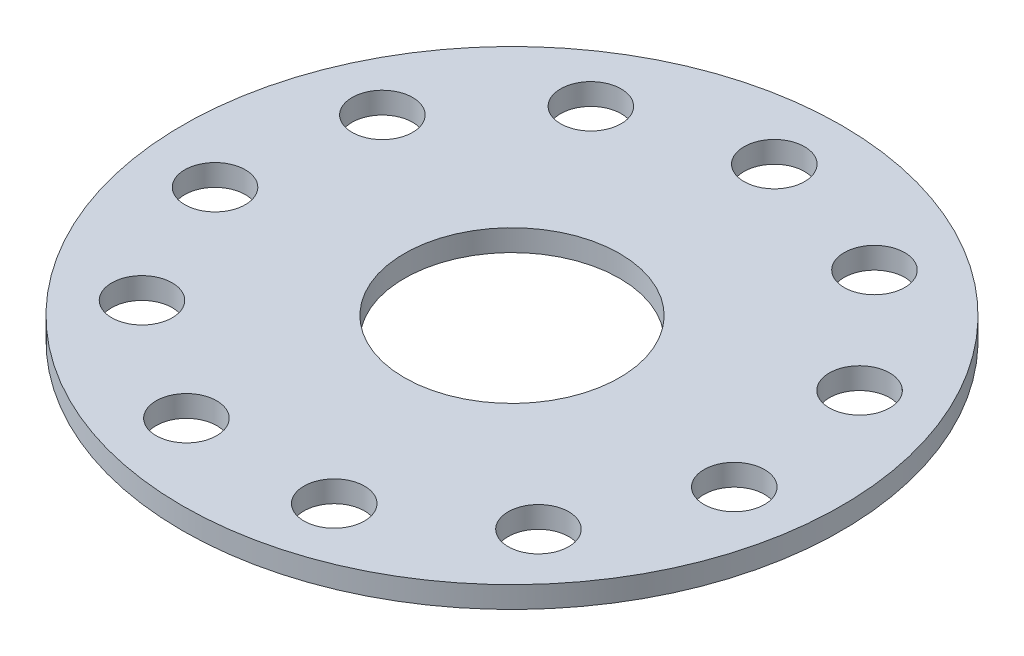
SolidWorks part; units mm, degrees
material "6061 Alloy"
ref_plane "Front Plane" through (0, 0, 0) normal (0, 0, 1) x (1, 0, 0)
ref_plane "Top Plane" through (0, 0, 0) normal (0, 1, 0) x (1, 0, 0)
ref_plane "Right Plane" through (0, 0, 0) normal (1, 0, 0) x (0, 0, -1)
sketch "Sketch1" plane through (0, 0, 0) normal (0, 1, 0) x (1, 0, 0)
  circle A0 centre (0, 0) radius 24.5
  circle A9 centre (0, 0) radius 8
  point P7 (0, 24.5)
  dimension "D1" = 49
  dimension "D2" = 16
extrude "Boss-Extrude1" add sketch "Sketch1" along normal blind 1.6002
sketch "Sketch3" plane through (0, 1.6002, 0) normal (0, 1, 0) x (1, 0, 0)
  line L53 (0, 19.5) -> (0, 24.5) construction
  circle A0 centre (0, 19.5) radius 2.25
  circle A3 centre (0, 0) radius 24.5 construction
  dimension "D1" = 4.5
  dimension "D2" = 5
extrude "Cut-Extrude1" cut sketch "Sketch3" against normal through all
pattern_circular "CirPattern1" count 11 over 360 about axis through (0, 0, 0) along (0, 1, 0) of "Cut-Extrude1"
equation "\"shaft_diameter\"=12"
equation "\"outerdiameter\"=49"
equation "\"numberofbars\"= 11"
equation "\"t\"= 20"
equation "\"width\"=1.5"
equation "\"bardiameter\"= 4.50"
equation "\"D1@Sketch1\"=\"outerdiameter\""
equation "\"centerdepth\"= 5"
equation "\"D1@Boss-Extrude1\"= \"t\""
equation "\"key_width\"=4"
equation "\"key_height\"= 2.5"
equation "\"D2@Sketch3\"=\"centerdepth\""
equation "\"RF1\"= 0.25"
equation "\"D1@Sketch3\"=\"bardiameter\""
equation "\"D1@CirPattern1\"=\"numberofbars\""
